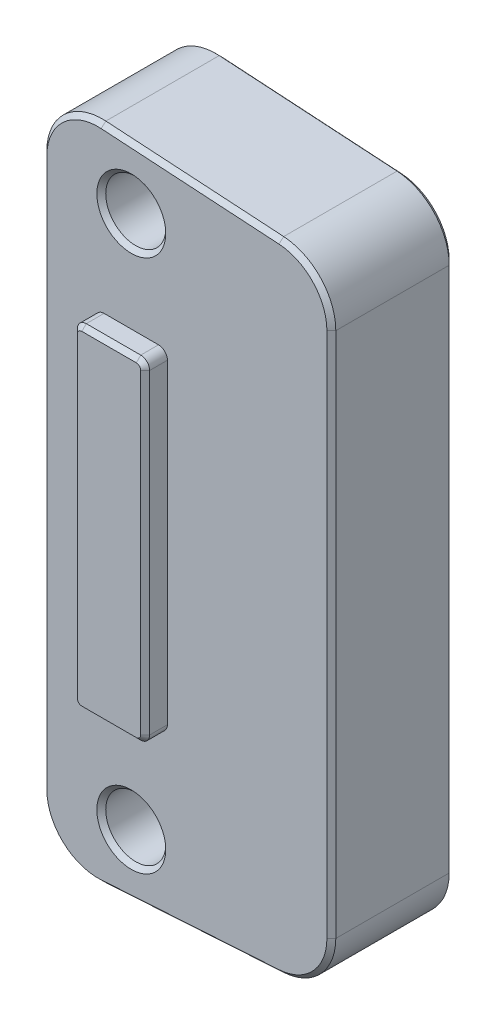
SolidWorks part; units mm, degrees
ref_plane "Front Plane" through (0, 0, 0) normal (0, 0, 1) x (1, 0, 0)
ref_plane "Top Plane" through (0, 0, 0) normal (0, 1, 0) x (1, 0, 0)
ref_plane "Right Plane" through (0, 0, 0) normal (1, 0, 0) x (0, 0, -1)
sketch "Sketch1" plane through (0, 0, 0) normal (0, 0, 1) x (1, 0, 0)
  line L0 (-13, -30) -> (-13, 30)
  line L2 (13, 28.375) -> (13, -28.375)
  line L4 (3.2, -17.75) -> (3.2, -12.35)
  line L5 (3.2, -12.35) -> (9.2, -12.35)
  line L6 (9.2, -12.35) -> (9.2, 12.35)
  line L7 (9.2, 12.35) -> (3.2, 12.35)
  line L8 (3.2, 12.35) -> (3.2, 17.75)
  line L9 (3.2, 17.75) -> (4.5, 17.75)
  line L10 (4.5, 17.75) -> (4.5, 15.548)
  line L11 (4.5, 15.548) -> (5.34, 14.15)
  line L12 (5.34, 14.15) -> (8.29, 14.15)
  line L13 (8.29, 14.15) -> (9.79, 15.65)
  line L14 (9.79, 15.65) -> (11, 15.65)
  line L15 (11, 15.65) -> (11, -15.65)
  line L16 (11, -15.65) -> (9.79, -15.65)
  line L17 (9.79, -15.65) -> (8.29, -14.15)
  line L18 (8.29, -14.15) -> (5.34, -14.15)
  line L19 (5.34, -14.15) -> (4.5, -15.548)
  line L20 (4.5, -15.548) -> (4.5, -17.75)
  line L21 (4.5, -17.75) -> (3.2, -17.75)
  line L22 (-5, -24) -> (-5, 24) construction
  line L23 (-13, 30) -> (13, 28.375)
  line L24 (13, -28.375) -> (-13, -30)
  line L25 (11, 28.5) -> (11, -28.5) construction
  circle A0 centre (-5, -24) radius 2.7
  circle A1 centre (-5, 24) radius 2.7
  point P26 (9.2, 0)
  point P27 (11, 0)
  point P28 (13, 0)
  point P29 (-5, 0)
  point P32 (0, 29.1875)
  point P34 (-13, 0)
  dimension "D16" = 5.4
  dimension "D1" = 31.3
  dimension "D2" = 1.21
  dimension "D3" = 24.7
  dimension "D4" = 2.71
  dimension "D5" = 5.66
  dimension "D6" = 6.5
  dimension "D7" = 7.8
  dimension "D8" = 31
  dimension "D9" = 35.5
  dimension "D10" = 48
  dimension "D11" = 60
  dimension "D12" = 8
  dimension "D13" = 2
  dimension "D14" = 16
  dimension "D15" = 1.8
  dimension "D17" = 57
extrude "Boss-Extrude1" add sketch "Sketch1" along normal blind 11
sketch "Sketch2" plane through (0, 0, 11) normal (0, 0, 1) x (1, 0, 0)
  line L0 (-5, -24) -> (-5, 24) construction
  line L1 (-8.25, -15) -> (-1.75, -15)
  line L2 (-8.25, -15) -> (-8.25, 15)
  line L3 (-8.25, 15) -> (-1.75, 15)
  line L4 (-1.75, -15) -> (-1.75, 15)
  point P4 (-5, -15)
  point P7 (-8.25, 0)
  dimension "D1" = 6.5
  dimension "D2" = 9
extrude "Boss-Extrude2" add sketch "Sketch2" along normal blind 2
sketch "Sketch3" plane through (0, 0, 11) normal (0, 0, 1) x (1, 0, 0)
  line L0 (4.5, 17.75) -> (3.2, 17.75) construction
  line L1 (3.2, -17.75) -> (11, -17.75)
  line L2 (3.2, -17.75) -> (3.2, 17.75)
  line L3 (3.2, 17.75) -> (11, 17.75)
  line L4 (11, -17.75) -> (11, 17.75)
  point P5 (3.2, 17.75)
extrude "Boss-Extrude3" add sketch "Sketch3" against normal blind 1
fillet "Fillet1" radius 5 4 edges at (-13, -30, 5.5) (13, -28.375, 5.5) (13, 28.375, 5.5) (-13, 30, 5.5)
fillet "Fillet2" radius 0.45 4 edges at (4.5, 17.75, 5) (3.2, 17.75, 5) (4.5, -17.75, 5) (3.2, -17.75, 5)
fillet "Fillet3" radius 0.8 6 edges at (5.34, 14.15, 5) (5.34, -14.15, 5) (-8.25, -15, 12) (-1.75, 15, 12) (-8.25, 15, 12) (-1.75, -15, 12)
fillet "Fillet4" radius 0.65 2 edges at (3.2, 12.35, 5) (3.2, -12.35, 5)
fillet "Fillet5" radius 1.85 2 edges at (9.2, 12.35, 5) (9.2, -12.35, 5)
chamfer "Chamfer1" distance 0.4 angle 45 56 edges at (3.3904, 12.5404, 0) (3.2, 15.15, 0) (3.3318, 17.6182, 0) (3.85, 17.75, 0) (4.3682, 17.6182, 0) (4.5, 16.424, 0) (4.8034, 15.043, 0) (5.3987, 14.2537, 0) (7.0413, 14.15, 0) (9.04, 14.9, 0) (10.395, 15.65, 0) (11, 0, 0) (10.395, -15.65, 0) (9.04, -14.9, 0) (7.0413, -14.15, 0) (5.3987, -14.2537, 0) (4.8034, -15.043, 0) (4.5, -16.424, 0) (4.3682, -17.6182, 0) (3.85, -17.75, 0) (3.3318, -17.6182, 0) (3.2, -15.15, 0) (3.3904, -12.5404, 0) (5.6, -12.35, 0) (8.6581, -11.8081, 0) (9.2, 0, 0) (8.6581, 11.8081, 0) (5.6, 12.35, 0) (-2.3, 24, 0) (13, 0, 0) (-13, 0, 0) (-2.3, -24, 0) (-2.3, 24, 11) (-2.3, -24, 11) (-1.9843, 14.7657, 13) (-5, 15, 13) (-1.75, 0, 13) (-8.0157, 14.7657, 13) (-1.9843, -14.7657, 13) (-8.25, 0, 13) (-5, -15, 13) (-8.0157, -14.7657, 13) (13, 0, 11) (-13, 0, 11) (0.3119, 29.168, 0) (0.3119, -29.168, 0) (11.6441, -27.1012, 0) (11.6441, 27.1012, 0) (-11.4235, 28.3219, 0) (-11.4235, -28.3219, 0) (11.6441, 27.1012, 11) (0.3119, 29.168, 11) (-11.4235, 28.3219, 11) (11.6441, -27.1012, 11) (0.3119, -29.168, 11) (-11.4235, -28.3219, 11)
